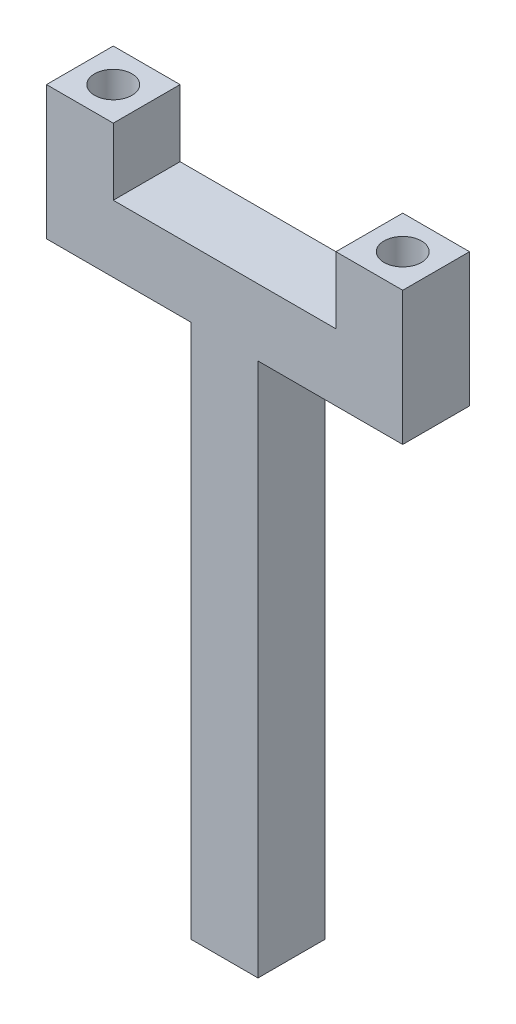
SolidWorks part; units mm, degrees
ref_plane "Front Plane" through (0, 0, 0) normal (0, 0, 1) x (1, 0, 0)
ref_plane "Top Plane" through (0, 0, 0) normal (0, 1, 0) x (1, 0, 0)
ref_plane "Right Plane" through (0, 0, 0) normal (1, 0, 0) x (0, 0, -1)
sketch "Sketch1" plane through (0, 0, 0) normal (0, 0, 1) x (1, 0, 0)
  line L0 (12.5, 75) -> (20, 75)
  line L2 (3.75, 60) -> (3.75, 0)
  line L3 (3.75, 0) -> (-3.75, 0)
  line L5 (0, 0) -> (0, 67.5) construction
  line L7 (-12.5, 75) -> (-20, 75)
  line L9 (-3.75, 60) -> (-3.75, 0)
  line L11 (-20, 75) -> (-20, 60)
  line L12 (-20, 60) -> (-3.75, 60)
  line L13 (20, 75) -> (20, 60)
  line L14 (20, 60) -> (3.75, 60)
  line L15 (12.5, 75) -> (12.5, 67.5)
  line L16 (12.5, 67.5) -> (0, 67.5)
  line L17 (0, 67.5) -> (-12.5, 67.5)
  line L18 (-12.5, 67.5) -> (-12.5, 75)
  point P6 (0, 66.523)
  point P14 (0, 0)
  point P16 (12.5, 67.4853)
  dimension "D1" = 7.5
  dimension "D2" = 60
  dimension "D3" = 40
  dimension "D4" = 7.5
  dimension "D5" = 15
  dimension "D6" = 7.5
extrude "Boss-Extrude1" add sketch "Sketch1" along normal blind 7.5
sketch "Sketch3" plane through (0, 75, 0) normal (0, 1, 0) x (1, 0, 0)
  line L0 (-20, 0) -> (-12.5, -7.5) construction
  line L1 (-12.5, -7.5) -> (12.5, 0) construction
  line L2 (12.5, 0) -> (20, -7.5) construction
  circle A0 centre (-16.25, -3.75) radius 2.1
  circle A1 centre (16.25, -3.75) radius 2.1
  point P5 (16.25, -3.75)
  point P17 (-16.25, -3.75)
  dimension "D1" = 4.2
  dimension "D2" = 32.5
extrude "Cut-Extrude1" cut sketch "Sketch3" against normal blind 5
